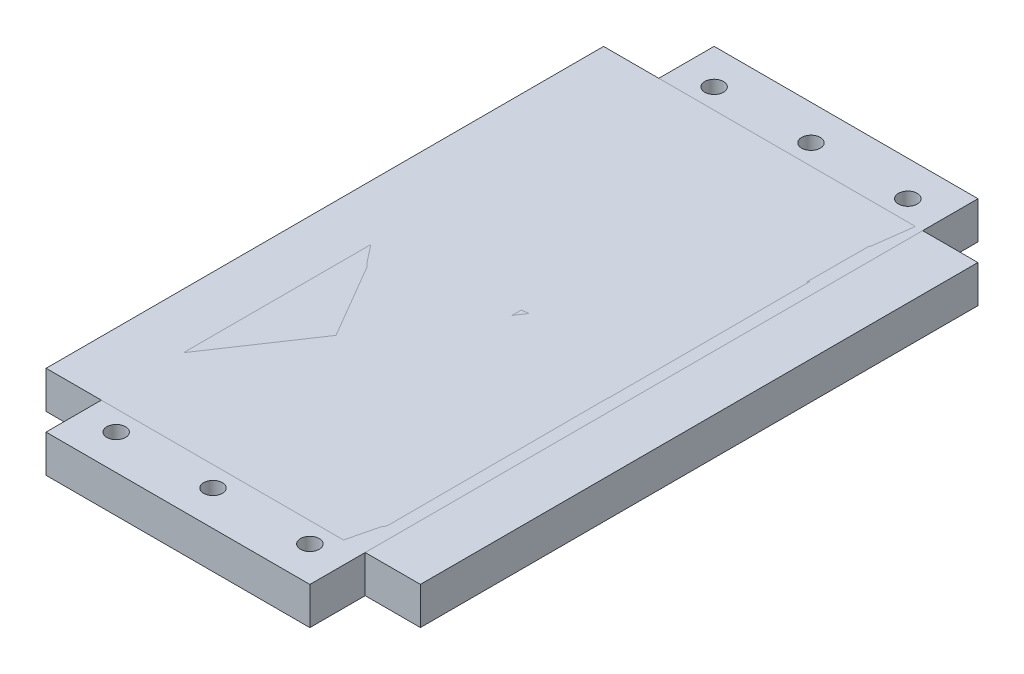
SolidWorks part; units mm, degrees
other "Part"
other "Stock"
ref_plane "Front Plane" through (0, 0, 0) normal (0, 0, 1) x (1, 0, 0)
ref_plane "Top Plane" through (0, 0, 0) normal (0, 1, 0) x (1, 0, 0)
ref_plane "Right Plane" through (0, 0, 0) normal (1, 0, 0) x (0, 0, -1)
sketch "Sketch1" plane through (0, 0, 0) normal (0, 1, 0) x (1, 0, 0)
  line L0 (28.2, 0) -> (28.2, -142.8) construction
  line L1 (0, 0) -> (56.4, 0)
  line L2 (0, 0) -> (0, -142.8)
  line L3 (0, -142.8) -> (56.4, -142.8)
  line L4 (56.4, 0) -> (56.4, -142.8)
  line L5 (0, -71.4) -> (56.4, -71.4) construction
  dimension "D1" = 56.4
  dimension "D2" = 142.8
extrude "Boss-Extrude1" add sketch "Sketch1" along normal blind 8
sketch "Sketch2" plane through (0, 8, 0) normal (0, 1, 0) x (1, 0, 0)
  line L0 (0, -71.4) -> (56.4, -71.4) construction
  line L1 (0, 0) -> (0, -142.8) construction
  line L2 (56.4, -142.8) -> (56.4, 0) construction
  line L3 (28.2, 0) -> (28.2, -142.8) construction
  line L4 (56.4, 0) -> (0, 0) construction
  line L5 (0, -142.8) -> (56.4, -142.8) construction
  line L6 (0, -43.2) -> (56.4, -43.2) construction
  circle A0 centre (28.2, -43.2) radius 16
  dimension "D2" = 32
  dimension "D1" = 28.2
extrude "Cut-Extrude1" cut sketch "Sketch2" against normal blind 6
sketch "Sketch3" plane through (0, 2, 0) normal (0, 1, 0) x (1, 0, 0)
  circle A0 centre (28.2, -43.2) radius 10
  dimension "D1" = 20
extrude "Cut-Extrude2" cut sketch "Sketch3" against normal through all
sketch "Sketch4" plane through (0, 8, 0) normal (0, 1, 0) x (1, 0, 0)
  line L0 (56.4, 0) -> (0, 0) construction
  line L1 (28.2, 0) -> (28.2, -86.1901) construction
  line L2 (0, -43.2) -> (56.4, -43.2) construction
  line L3 (0, 0) -> (0, -142.8) construction
  line L4 (56.4, -142.8) -> (56.4, 0) construction
  line L5 (0, -71.4) -> (56.4, -71.4) construction
  circle A0 centre (4.58, -19.58) radius 2
  circle A1 centre (51.82, -19.58) radius 2
  circle A2 centre (51.82, -66.82) radius 2
  circle A3 centre (4.58, -66.82) radius 2
  dimension "D4" = 4
  dimension "D1" = 23.62
  dimension "D2" = 28.2
  dimension "D3" = 23.62
extrude "Cut-Extrude3" cut sketch "Sketch4" against normal through all
sketch "Sketch5" plane through (0, 8, 0) normal (0, 1, 0) x (1, 0, 0)
  line L0 (0, -71.4) -> (56.4, -71.4) construction
  line L1 (0, 0) -> (0, -142.8) construction
  line L2 (56.4, -142.8) -> (56.4, 0) construction
  line L3 (0, -99.6) -> (56.4, -99.6) construction
  line L4 (28.2, 0) -> (28.2, -142.8) construction
  line L5 (56.4, 0) -> (0, 0) construction
  line L6 (0, -142.8) -> (56.4, -142.8) construction
  circle A0 centre (28.2, -99.6) radius 12
  point P14 (28.2, -99.6)
  dimension "D2" = 24
  dimension "D1" = 28.2
extrude "Cut-Extrude4" cut sketch "Sketch5" against normal through all
ref_plane "Plane1" through (0, 0, 71.4) normal (0, 0, 1) x (1, 0, 0)
mirror "Mirror1" about plane through (0, 0, 71.4) normal (0, 0, 1) of "Cut-Extrude3"
fillet "Fillet2" [suppressed] radius 3
sketch "Sketch6" plane through (0, 8, 0) normal (0, 1, 0) x (1, 0, 0)
  line L0 (56.4, -142.8) -> (56.4, 0) construction
  line L1 (0, 0) -> (56.4, 0) construction
  line L2 (0, 0) -> (0, -142.8) construction
  line L3 (0, -142.8) -> (56.4, -142.8) construction
  line L4 (56.4, 0) -> (56.4, -142.8) construction
  line L5 (56.4, 0) -> (0, 0) construction
  line L6 (0, 0) -> (0, -142.8) construction
  line L7 (0, -142.8) -> (56.4, -142.8) construction
  line L8 (0, -71.4) -> (56.4, -71.4) construction
  line L9 (28.2, 0) -> (28.2, -142.8) construction
  line L10 (0, 0) -> (56.4, -142.8) construction
  line L11 (0, -142.8) -> (56.4, 0) construction
  line L13 (-11.8, -11.825) -> (68.2, -11.825)
  line L14 (-11.8, -11.825) -> (-11.8, -130.975)
  line L15 (-11.8, -130.975) -> (68.2, -130.975)
  line L16 (68.2, -11.825) -> (68.2, -130.975)
  line L17 (-11.8, -11.825) -> (68.2, -130.975) construction
  line L18 (-11.8, -130.975) -> (68.2, -11.825) construction
  point P16 (28.2, -71.4)
  dimension "D1" = 80
  dimension "D2" = 119.15
extrude "Boss-Extrude2" add sketch "Sketch6" against normal blind 8 separate body
sketch "Sketch8" plane through (0, 8, 0) normal (0, 1, 0) x (1, 0, 0)
  line L0 (-11.8, -11.825) -> (-11.8, -130.975) construction
  line L1 (-11.8, -130.975) -> (68.2, -130.975) construction
  line L2 (-11.8, -11.825) -> (-11.8, -130.975)
  line L3 (-11.8, -130.975) -> (68.2, -130.975)
sketch "Sketch9" plane through (0, 8, 0) normal (0, 1, 0) x (1, 0, 0)
  line L0 (56.4, 0) -> (0, 0) construction
  line L1 (0, 0) -> (0, -142.8) construction
  line L2 (56.4, -142.8) -> (56.4, 0) construction
  line L3 (28.2, 0) -> (28.2, -70.1416) construction
  circle A0 centre (7.5, -7.5) radius 2
  circle A1 centre (28.2, -7.5) radius 2
  circle A2 centre (48.9, -7.5) radius 2
  dimension "D1" = 4
  dimension "D2" = 4
  dimension "D3" = 4
  dimension "D4" = 7.5
  dimension "D5" = 7.5
  dimension "D6" = 7.5
  dimension "D7" = 7.5
  dimension "D8" = 7.5
extrude "Cut-Extrude5" cut sketch "Sketch9" against normal blind 10
mirror "Mirror2" about plane through (0, 0, 71.4) normal (0, 0, 1) of "Cut-Extrude5"
sketch "Sketch10" plane through (0, 8, 0) normal (0, 1, 0) x (1, 0, 0)
  line L0 (0, -71.4) -> (56.4, -71.4) construction
  line L1 (0, 0) -> (0, -142.8) construction
  line L2 (56.4, -142.8) -> (56.4, 0) construction
  line L3 (28.2, 0) -> (28.2, -121.035) construction
  line L4 (56.4, 0) -> (0, 0) construction
  line L6 (-0.8, -69.4) -> (28.2, -69.4)
  line L7 (-0.8, -69.4) -> (-0.8, -73.4)
  line L8 (-0.8, -73.4) -> (28.2, -73.4)
  line L9 (28.2, -69.4) -> (28.2, -73.4)
  point P14 (28.2, -71.4)
  point P15 (28.2, -71.4)
  dimension "D1" = 29
  dimension "D2" = 4
extrude "Cut-Extrude6" cut sketch "Sketch10" against normal blind 3
